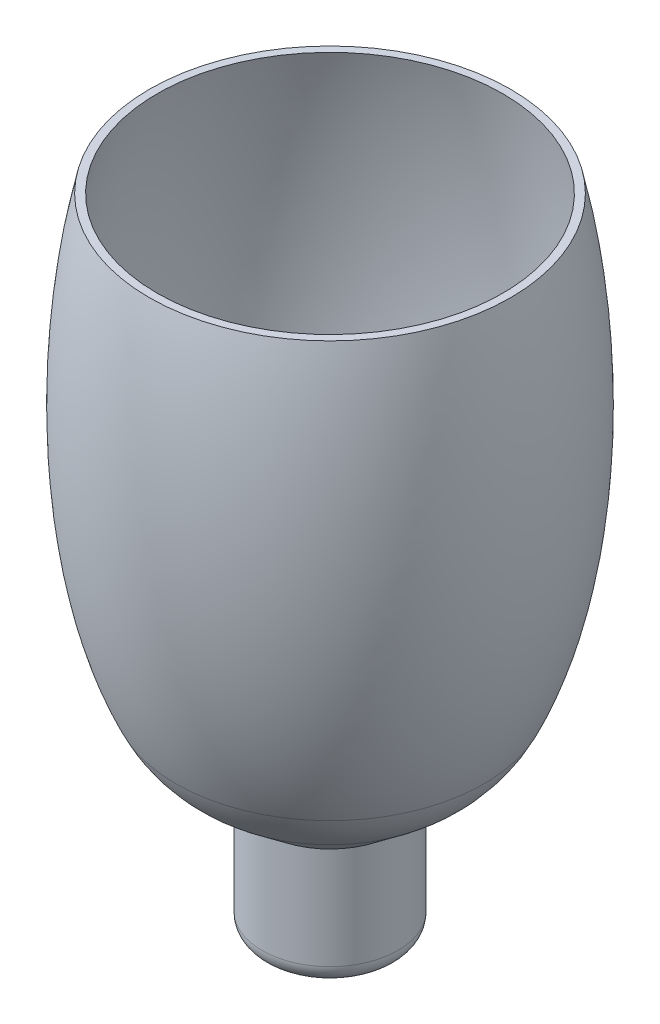
SolidWorks part; units mm, degrees
ref_plane "Front Plane" through (0, 0, 0) normal (0, 0, 1) x (1, 0, 0)
ref_plane "Top Plane" through (0, 0, 0) normal (0, 1, 0) x (1, 0, 0)
ref_plane "Right Plane" through (0, 0, 0) normal (1, 0, 0) x (0, 0, -1)
sketch "Sketch1" plane through (0, 0, 0) normal (0, 0, 1) x (1, 0, 0)
  line L0 (0, 0) -> (0, 32)
  line L1 (0, 32) -> (-18, 32)
  line L2 (-18, 32) -> (-18, 5)
  line L3 (-13, 0) -> (0, 0)
  arc A0 (-13, 0) -> (-18, 5) centre (-13, 5) cw
  dimension "D1" = 5
revolve "Revolve1" add sketch "Sketch1" angle 360 about L0
sketch "Sketch2" plane through (0, 0, 0) normal (0, 0, 1) x (1, 0, 0)
  line L0 (0, 32) -> (0, 169.7018)
  line L1 (18, 32) -> (-18, 32) construction
  line L2 (0, 169.7018) -> (-47.8459, 169.7018)
  line L3 (-30.7204, 41.9692) -> (-18, 32)
  line L4 (-18, 32) -> (0, 32)
  arc A0 (-30.7204, 41.9692) -> (-40.8096, 54.6359) centre (-9.1307, 69.517) cw
  spline S0 degree 3 poles (-47.8459, 169.7018) (-56.0272, 134.2446) (-55.3369, 85.5617) (-40.8096, 54.6359) knots 0 0 0 0 0.888015 0.888015 0.888015 0.888015
  point P12 (-42.2317, 77.433)
  point P13 (-47.8459, 169.7018)
  point P14 (-56.6263, 138.2145)
  point P15 (-48.0978, 63.8954)
  point P16 (-40.8096, 54.6359)
  point P17 (-52.5057, 137.7272)
  dimension "D1" = 35
revolve "Revolve2" add sketch "Sketch2" angle 360 about L0
shell "Shell1" thickness 2
